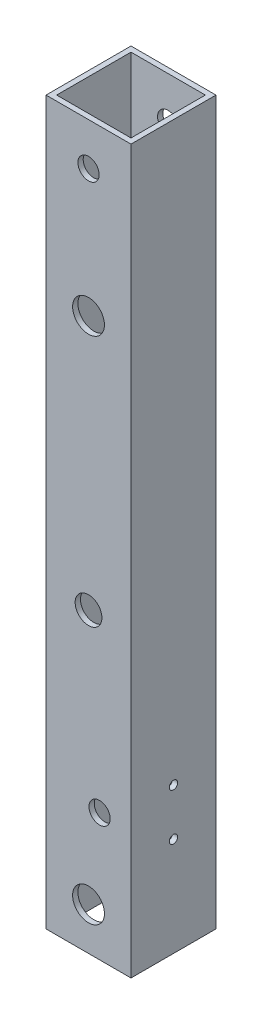
SolidWorks part; units mm, degrees
ref_plane "Front Plane" through (0, 0, 0) normal (0, 0, 1) x (1, 0, 0)
ref_plane "Top Plane" through (0, 0, 0) normal (0, 1, 0) x (1, 0, 0)
ref_plane "Right Plane" through (0, 0, 0) normal (1, 0, 0) x (0, 0, -1)
sketch "Sketch1" plane through (0, 0, 0) normal (0, 1, 0) x (1, 0, 0)
  line L1 (-12.7, 12.7) -> (12.7, 12.7)
  line L2 (-12.7, 12.7) -> (-12.7, -12.7)
  line L3 (-12.7, -12.7) -> (12.7, -12.7)
  line L4 (12.7, 12.7) -> (12.7, -12.7)
  line L5 (-12.7, 12.7) -> (12.7, -12.7) construction
  line L6 (-12.7, -12.7) -> (12.7, 12.7) construction
  line L7 (11.1125, -11.1125) -> (-11.1125, -11.1125)
  line L8 (11.1125, -11.1125) -> (11.1125, 11.1125)
  line L9 (11.1125, 11.1125) -> (-11.1125, 11.1125)
  line L10 (-11.1125, -11.1125) -> (-11.1125, 11.1125)
  line L11 (11.1125, -11.1125) -> (-11.1125, 11.1125) construction
  line L12 (11.1125, 11.1125) -> (-11.1125, -11.1125) construction
  point P0 (0, 0)
  point P6 (0, 0)
  dimension "D1" = 25.4
  dimension "D2" = 1.5875
extrude "Boss-Extrude1" add sketch "Sketch1" along normal blind 215.9
other "1in Square tube<1>"
sketch "Sketch2" plane through (0, 0, 12.7) normal (0, 0, 1) x (1, 0, 0)
  line L0 (0, 215.9) -> (0, 165.1) construction
  line L1 (-12.7, 215.9) -> (12.7, 215.9) construction
  line L2 (0, 165.1) -> (0, 88.9) construction
  line L3 (0, 88.9) -> (0, 12.7) construction
  line L4 (0, 12.7) -> (0, 0) construction
  circle A0 centre (0, 88.9) radius 4
  circle A1 centre (0, 165.1) radius 4.7625
  circle A2 centre (0, 12.7) radius 4.7625
  circle A3 centre (0, 203.2) radius 3.175
  dimension "D1" = 8
  dimension "D2" = 9.525
  dimension "D5" = 6.35
  dimension "D3" = 12.7
  dimension "D4" = 114.3
  dimension "D6" = 152.4
extrude "Cut-Extrude1" cut sketch "Sketch2" against normal through all
sketch "Sketch3" plane through (0, 0, 12.7) normal (0, 0, 1) x (1, 0, 0)
  line L1 (-12.7, 0) -> (12.7, 0) construction
  line L2 (12.7, 215.9) -> (12.7, 0) construction
  circle A0 centre (3.302, 38.1) radius 3.175
  dimension "D1" = 6.35
  dimension "D2" = 9.398
  dimension "D3" = 38.1
extrude "Cut-Extrude2" cut sketch "Sketch3" against normal through all
sketch "Sketch5" plane through (-12.7, 0, 0) normal (-1, 0, 0) x (0, 0, 1)
  line L0 (0, 43.6) -> (0, 29.6) construction
  line L2 (11.1125, 38.1) -> (12.7, 38.1) construction
  circle A0 centre (0, 43.6) radius 1.25
  circle A1 centre (0, 29.6) radius 1.25
  point P9 (0, 36.6)
  dimension "D2" = 2.5
  dimension "D1" = 1.5
  dimension "D3" = 14
extrude "Cut-Extrude3" cut sketch "Sketch5" against normal through all
